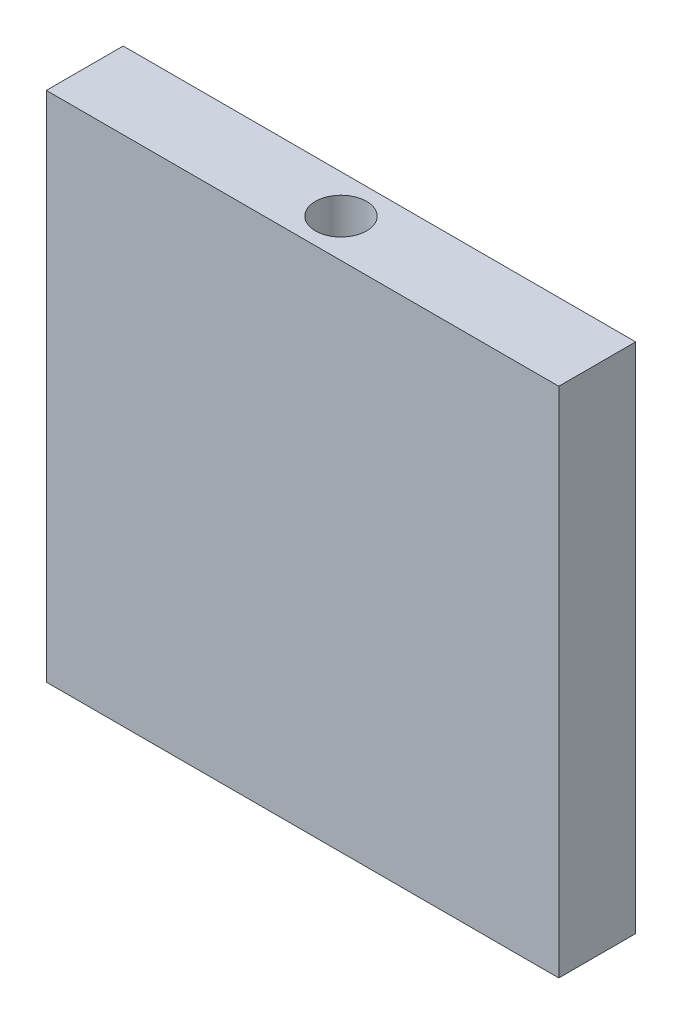
SolidWorks part; units mm, degrees
ref_plane "Front Plane" through (0, 0, 0) normal (0, 0, 1) x (1, 0, 0)
ref_plane "Top Plane" through (0, 0, 0) normal (0, 1, 0) x (1, 0, 0)
ref_plane "Right Plane" through (0, 0, 0) normal (1, 0, 0) x (0, 0, -1)
sketch "Sketch1" plane through (0, 0, 0) normal (0, 1, 0) x (1, 0, 0)
  line L1 (-12.7, 1.905) -> (12.7, 1.905)
  line L2 (-12.7, 1.905) -> (-12.7, -1.905)
  line L3 (-12.7, -1.905) -> (12.7, -1.905)
  line L4 (12.7, 1.905) -> (12.7, -1.905)
  line L5 (-12.7, 1.905) -> (12.7, -1.905) construction
  line L6 (-12.7, -1.905) -> (12.7, 1.905) construction
  circle A0 centre (0, 0) radius 1.27
  dimension "D1" = 2.54
  dimension "D2" = 3.81
  dimension "D3" = 25.4
extrude "Boss-Extrude1" add sketch "Sketch1" along normal blind 25.4
